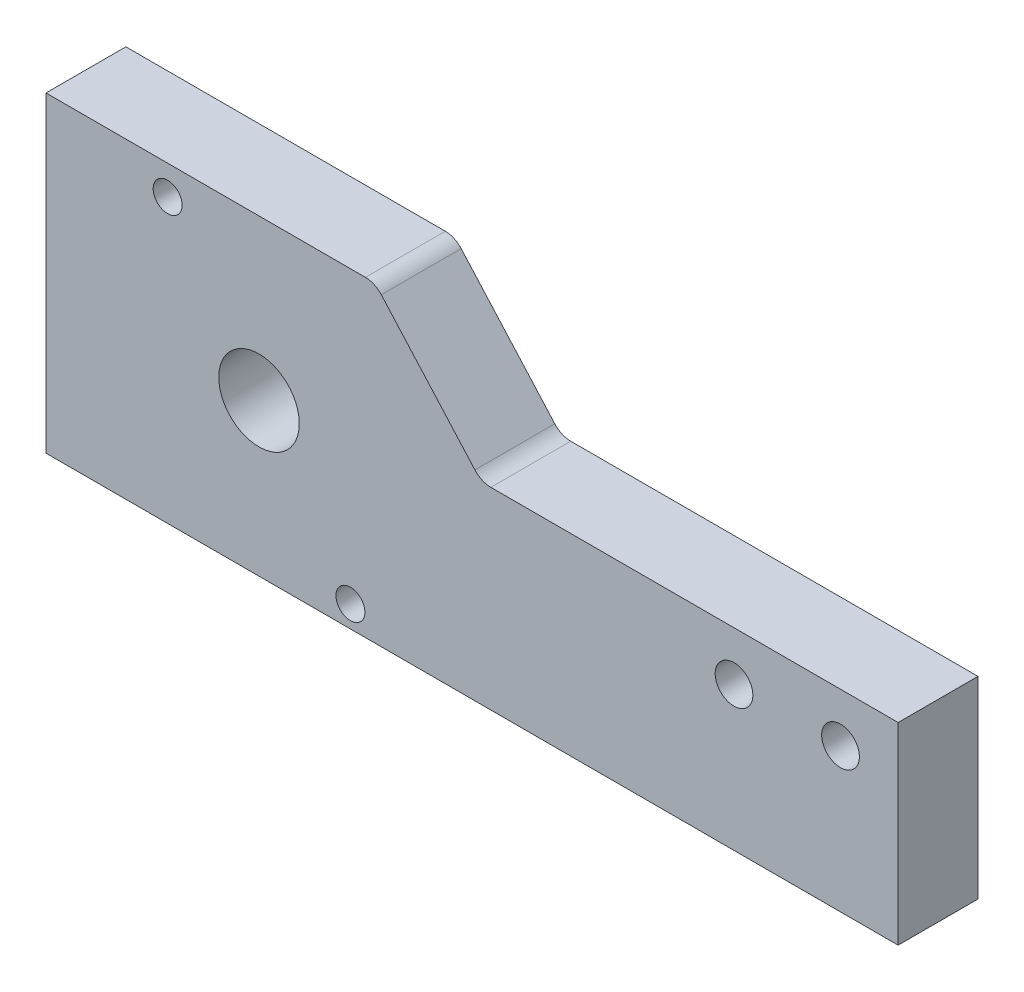
SolidWorks part; units mm, degrees
ref_plane "Front Plane" through (0, 0, 0) normal (0, 0, 1) x (1, 0, 0)
ref_plane "Top Plane" through (0, 0, 0) normal (0, 1, 0) x (1, 0, 0)
ref_plane "Right Plane" through (0, 0, 0) normal (1, 0, 0) x (0, 0, -1)
sketch "Sketch1" plane through (0, 0, 0) normal (0, 0, 1) x (1, 0, 0)
  line L1 (50.8, -25.4) -> (-50.8, -25.4)
  line L2 (50.8, -25.4) -> (50.8, 25.4)
  line L3 (50.8, 25.4) -> (-50.8, 25.4)
  line L4 (-50.8, -25.4) -> (-50.8, 25.4)
  line L5 (50.8, -25.4) -> (-50.8, 25.4) construction
  line L6 (50.8, 25.4) -> (-50.8, -25.4) construction
  point P0 (0, 0)
  dimension "D1" = 101.6
  dimension "D2" = 50.8
extrude "Boss-Extrude1" add sketch "Sketch1" along normal blind 9.525
sketch "Sketch3" plane through (0, 0, 9.525) normal (0, 0, 1) x (1, 0, 0)
  line L0 (-36.298, 21.9139) -> (-14.502, -9.2139) construction
  line L1 (50.8, 25.4) -> (-50.8, 25.4) construction
  circle A0 centre (-25.4, 6.35) radius 19 construction
  point P8 (-36.298, 21.9139)
  point P9 (-14.502, -9.2139)
  dimension "D1" = 38
  dimension "D2" = 25.4
  dimension "D3" = 6.35
  dimension "D4" = 55
sketch "Sketch6" plane through (0, 0, 0) normal (0, 0, 1) x (1, 0, 0)
  line L0 (-50.8, 25.4) -> (-50.8, -25.4) construction
  line L1 (-50.8, -25.4) -> (50.8, -25.4) construction
  circle A0 centre (-25.4, 6.35) radius 4.8 construction
  circle A1 centre (-25.4, 6.35) radius 4.8
  point P8 (-27.0981, 10.6379)
  point P9 (-20.85, 7.9694)
  dimension "D1" = 9.6
  dimension "D2" = 25.4
  dimension "D4" = 9.6
  dimension "D3" = 31.75
extrude "Cut-Extrude1" cut sketch "Sketch6" along normal through all contours A1
hole_wizard "Tap Drill for #8-32 Tap1" positions "Sketch3" profile "Sketch5" hole size "#8-32" standard "ANSI Inch" end condition through all
sketch "Sketch5" plane through (-14.502, -9.2139, 9.525) normal (1, 0, 0) x (0, -1, 0)
  line L0 (0, 0) -> (0, 9.525)
  line L1 (0, 9.525) -> (1.7272, 9.525)
  line L2 (1.7272, 9.525) -> (1.7272, 0)
  line L5 (1.7272, 0) -> (0, 0)
  line L11 (0, -6.35) -> (0, 107.95) construction
  dimension "Thru Hole Dia." = 3.4544
  dimension "Thru Hole Depth" = 9.525
sketch "Sketch7" plane through (0, 0, 0) normal (0, 0, -1) x (-1, 0, 0)
  line L0 (-50.8, -25.4) -> (-50.8, 25.4) construction
  line L1 (50.8, -25.4) -> (-50.8, -25.4)
  line L2 (50.8, -25.4) -> (50.8, -6.35)
  line L3 (50.8, -6.35) -> (-50.8, -6.35)
  line L4 (-50.8, -25.4) -> (-50.8, -6.35)
  dimension "D1" = 19.05
hole_wizard "#8 Clearance Hole1" positions "Sketch8" profile "Sketch9" hole size "#8" standard "ANSI Inch" end condition through all
sketch "Sketch8" plane through (0, 0, 9.525) normal (0, 0, 1) x (1, 0, 0)
  circle A0 centre (31.2318, 5.3435) radius 2.2479 construction
  circle A1 centre (43.9318, 5.3435) radius 2.2479 construction
  point P0 (31.2318, 5.3435)
  point P3 (43.9318, 5.3435)
sketch "Sketch9" plane through (31.2318, 5.3435, 9.525) normal (1, 0, 0) x (0, -1, 0)
  line L0 (0, 0) -> (0, 9.525)
  line L1 (0, 9.525) -> (2.2479, 9.525)
  line L2 (2.2479, 9.525) -> (2.2479, 0)
  line L5 (2.2479, 0) -> (0, 0)
  line L11 (0, -6.35) -> (0, 107.95) construction
  dimension "Thru Hole Dia." = 4.4958
  dimension "Thru Hole Depth" = 9.525
sketch "Sketch10" plane through (0, 0, 9.525) normal (0, 0, 1) x (1, 0, 0)
  line L0 (50.8, -25.4) -> (50.8, -6.35) construction
  line L1 (-50.8, -48.9404) -> (50.8, -48.9404)
  line L2 (-50.8, -48.9404) -> (-50.8, -11.8015)
  line L3 (-50.8, -11.8015) -> (50.8, -11.8015)
  line L4 (50.8, -48.9404) -> (50.8, -11.8015)
  line L5 (-50.8, -48.9404) -> (50.8, -11.8015) construction
  line L6 (-50.8, -11.8015) -> (50.8, -48.9404) construction
  point P0 (0, -30.371)
extrude "Cut-Extrude2" cut sketch "Sketch10" against normal through all
sketch "Sketch11" plane through (0, 0, 9.525) normal (0, 0, 1) x (1, 0, 0)
  line L0 (50.8, 11.1939) -> (1.0961, 11.1939)
  line L1 (50.8, -11.8015) -> (50.8, 25.4) construction
  line L2 (1.0961, 11.1939) -> (-11.5766, 25.4)
  line L3 (50.8, 25.4) -> (-50.8, 25.4) construction
  line L4 (50.8, 11.1939) -> (50.8, 25.4)
  line L5 (50.8, 25.4) -> (-11.5766, 25.4)
extrude "Cut-Extrude3" cut sketch "Sketch11" against normal through all
fillet "Fillet1" radius 2.54 2 edges at (1.0961, 11.1939, 4.7625) (-11.5766, 25.4, 4.7625)
